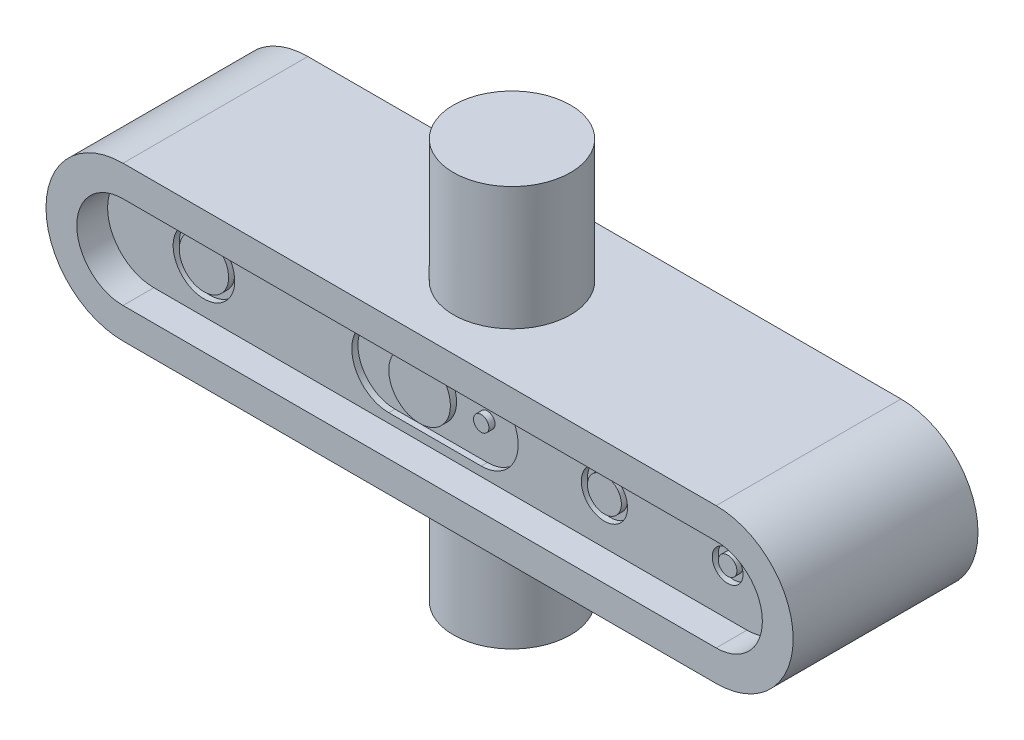
SolidWorks part; units mm, degrees
ref_plane "Front Plane" through (0, 0, 0) normal (0, 0, 1) x (1, 0, 0)
ref_plane "Top Plane" through (0, 0, 0) normal (0, 1, 0) x (1, 0, 0)
ref_plane "Right Plane" through (0, 0, 0) normal (1, 0, 0) x (0, 0, -1)
sketch "Sketch1" plane through (0, 0, 0) normal (0, 0, 1) x (1, 0, 0)
  line L0 (0, 0) -> (0, 33416.6993) construction
  line L1 (-48.1361, 12.5) -> (48.1361, 12.5)
  line L3 (48.1361, -12.5) -> (-48.1361, -12.5)
  arc A0 (-48.1361, 12.5) -> (-48.1361, -12.5) centre (-48.1361, 0) ccw
  arc A1 (48.1361, 12.5) -> (48.1361, -12.5) centre (48.1361, 0) cw
  dimension "D1" = 25
extrude "Boss-Extrude1" add sketch "Sketch1" along normal blind 25
sketch "Sketch2" plane through (0, 0, 25) normal (0, 0, 1) x (1, 0, 0)
  line L0 (-48.1361, 12.5) -> (48.1361, 12.5)
  line L1 (-48.1361, -12.5) -> (48.1361, -12.5)
  arc A0 (-48.1361, 12.5) -> (-48.1361, -12.5) centre (-48.1361, 0) ccw
  arc A1 (48.1361, -12.5) -> (48.1361, 12.5) centre (48.1361, 0) ccw
  dimension "D1" = 12.5
extrude "Extrude-Thin2" add sketch "Sketch2" along normal blind 5 thin
sketch "Sketch3" plane through (0, 0, 25) normal (0, 0, 1) x (1, 0, 0)
  line L0 (-10, 6) -> (5, 6)
  line L2 (5, -6) -> (-10, -6)
  circle A0 centre (-40, 0) radius 5
  arc A1 (-10, 6) -> (-10, -6) centre (-10, 0) ccw
  arc A2 (5, -6) -> (5, 6) centre (5, 0) ccw
  circle A3 centre (25, 0) radius 3.75
  circle A4 centre (45, 0) radius 2.5
  dimension "D1" = 10
  dimension "D3" = 7.5
  dimension "D4" = 5
  dimension "D2" = 15
  dimension "D5" = 30
  dimension "D6" = 20
  dimension "D7" = 20
extrude "Cut-Extrude1" cut sketch "Sketch3" against normal blind 1
sketch "Sketch4" plane through (0, 0, 24) normal (0, 0, 1) x (1, 0, 0)
  circle A0 centre (-5, 0) radius 5
  arc A1 (-10, 6) -> (-10, -6) centre (-10, 0) ccw construction
  circle A2 centre (5, 0) radius 1.25
  circle A4 centre (-40, 0) radius 4
  circle A6 centre (25, 0) radius 2.75
  circle A7 centre (45, 0) radius 1.5
  dimension "D1" = 5
  dimension "D3" = 2.5
  dimension "D2" = 10
extrude "Boss-Extrude2" add sketch "Sketch4" along normal blind 1
sketch "Sketch5" plane through (0, 12.5, 0) normal (0, 1, 0) x (1, 0, 0)
  circle A0 centre (0, -15) radius 9.5
extrude "Boss-Extrude4" add sketch "Sketch5" along normal blind 20
sketch "Sketch7" plane through (0, -12.5, 0) normal (0, -1, 0) x (1, 0, 0)
  circle A0 centre (0, 15) radius 9.5
extrude "Boss-Extrude5" add sketch "Sketch7" along normal blind 20
